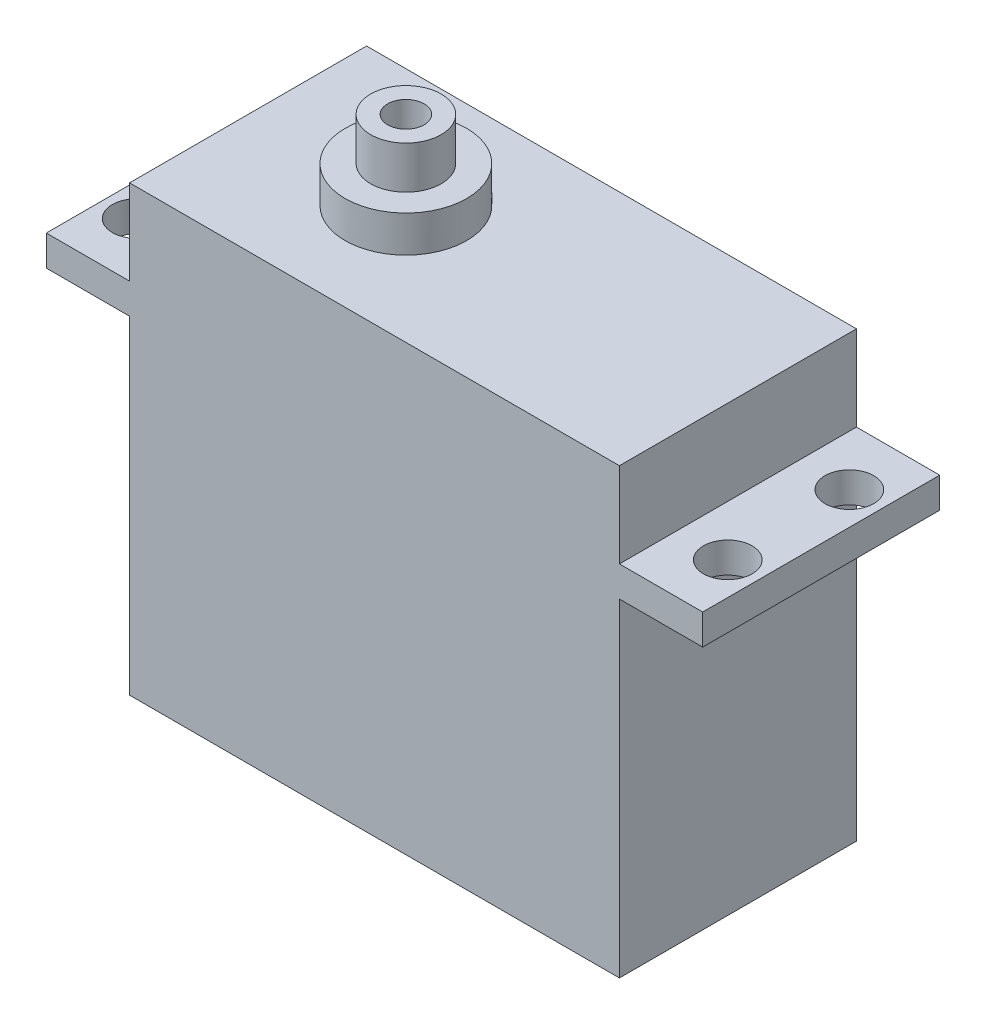
SolidWorks part; units mm, degrees
ref_plane "前视基准面" through (0, 0, 0) normal (0, 0, 1) x (1, 0, 0)
ref_plane "上视基准面" through (0, 0, 0) normal (0, 1, 0) x (1, 0, 0)
ref_plane "右视基准面" through (0, 0, 0) normal (1, 0, 0) x (0, 0, -1)
sketch "草图1" plane through (0, 0, 0) normal (0, 1, 0) x (1, 0, 0)
  line L1 (-20.15, -9.75) -> (20.15, -9.75)
  line L2 (-20.15, -9.75) -> (-20.15, 9.75)
  line L3 (-20.15, 9.75) -> (20.15, 9.75)
  line L4 (20.15, -9.75) -> (20.15, 9.75)
  line L5 (-20.15, -9.75) -> (20.15, 9.75) construction
  line L6 (-20.15, 9.75) -> (20.15, -9.75) construction
  point P0 (0, 0)
  dimension "D1" = 19.5
  dimension "D2" = 40.3
extrude "凸台-拉伸1" add sketch "草图1" along normal blind 27
sketch "草图2" plane through (0, 27, 0) normal (0, 1, 0) x (1, 0, 0)
  line L1 (-27, -9.75) -> (27, -9.75)
  line L2 (-27, -9.75) -> (-27, 9.75)
  line L3 (-27, 9.75) -> (27, 9.75)
  line L4 (27, -9.75) -> (27, 9.75)
  line L5 (-27, -9.75) -> (27, 9.75) construction
  line L6 (-27, 9.75) -> (27, -9.75) construction
  point P0 (0, 0)
  dimension "D1" = 19.5
  dimension "D2" = 54
extrude "凸台-拉伸2" add sketch "草图2" along normal blind 2.5
sketch "草图3" plane through (0, 29.5, 0) normal (0, 1, 0) x (1, 0, 0)
  line L0 (0, 12.1099) -> (0, 0) construction
  line L1 (0, 0) -> (30.5157, 0) construction
  circle A0 centre (24.315, 5) radius 2
  circle A1 centre (-24.315, 5) radius 2
  circle A2 centre (24.315, -5) radius 2
  circle A3 centre (-24.315, -5) radius 2
  dimension "D1" = 4
  dimension "D2" = 10
  dimension "D3" = 48.63
extrude "切除-拉伸1" cut sketch "草图3" against normal up to next
sketch "草图4" plane through (0, 29.5, 0) normal (0, 1, 0) x (1, 0, 0)
  line L1 (-20.15, -9.75) -> (20.15, -9.75)
  line L2 (-20.15, -9.75) -> (-20.15, 9.75)
  line L3 (-20.15, 9.75) -> (20.15, 9.75)
  line L4 (20.15, -9.75) -> (20.15, 9.75)
  line L5 (-20.15, -9.75) -> (20.15, 9.75) construction
  line L6 (-20.15, 9.75) -> (20.15, -9.75) construction
  line L7 (27, 9.75) -> (-27, 9.75) construction
  point P0 (0, 0)
  dimension "D1" = 19.5
  dimension "D2" = 40.3
extrude "凸台-拉伸3" add sketch "草图4" along normal blind 7
sketch "草图6" plane through (0, 36.5, 0) normal (0, 1, 0) x (1, 0, 0)
  line L0 (0, 0) -> (-7.165, 0) construction
  circle A0 centre (-7.165, 0) radius 2.9
  circle A1 centre (-7.165, 0) radius 1.5
  circle A2 centre (-24.315, 5) radius 2 construction
  dimension "D1" = 5.8
  dimension "D2" = 3
  dimension "D3" = 17.15
extrude "凸台-拉伸4" add sketch "草图6" along normal blind 6.5
sketch "草图7" plane through (0, 36.5, 0) normal (0, 1, 0) x (1, 0, 0)
  circle A0 centre (-7.165, 0) radius 2.9 construction
  circle A1 centre (-7.165, 0) radius 2.9
  circle A2 centre (-7.165, 0) radius 5
  dimension "D1" = 10
extrude "凸台-拉伸5" add sketch "草图7" along normal blind 3
sketch "草图8" plane through (-20.15, 0, 0) normal (-1, 0, 0) x (0, 0, 1)
  line L0 (0, 0) -> (0, 3.49) construction
  line L2 (-3.4949, 1.9157) -> (3.4949, 1.9157)
  line L3 (-3.4949, 1.9157) -> (-3.4949, 5.0643)
  line L4 (-3.4949, 5.0643) -> (3.4949, 5.0643)
  line L5 (3.4949, 1.9157) -> (3.4949, 5.0643)
  line L6 (-3.4949, 1.9157) -> (3.4949, 5.0643) construction
  line L7 (-3.4949, 5.0643) -> (3.4949, 1.9157) construction
extrude "凸台-拉伸6" add sketch "草图8" along normal blind 6
